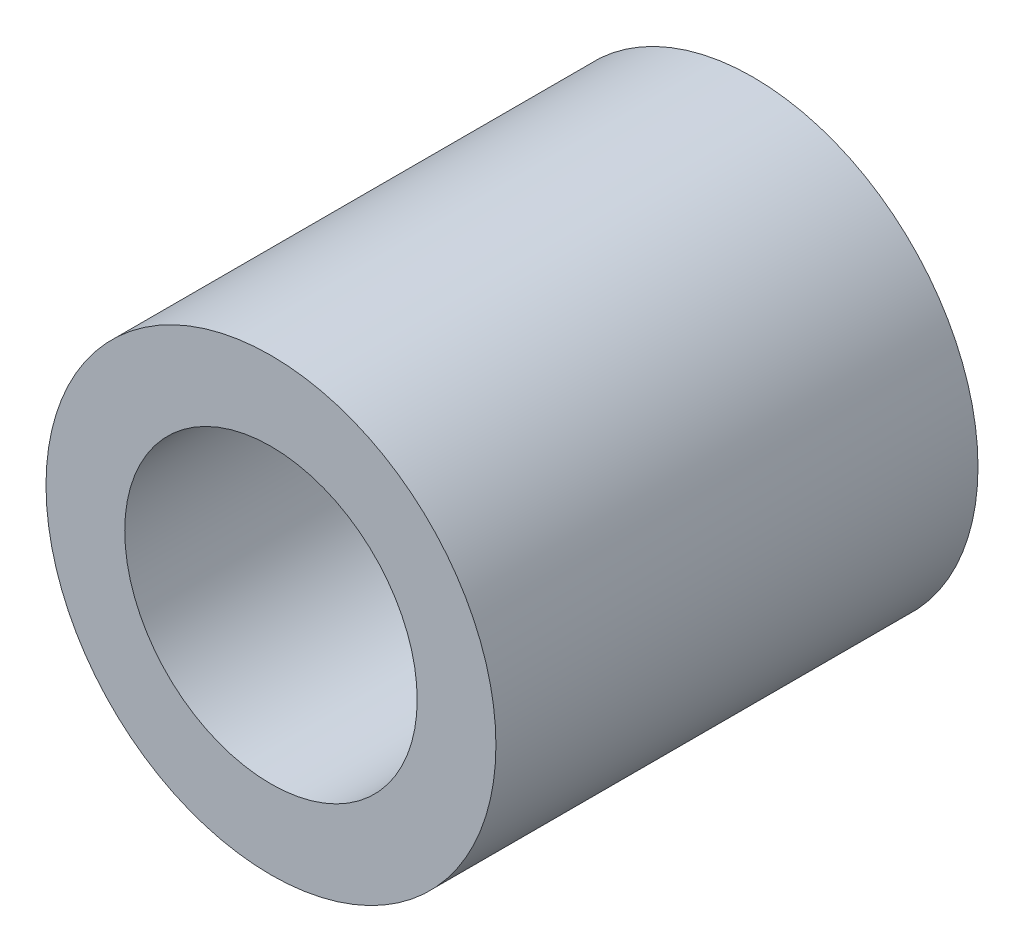
SolidWorks part; units mm, degrees
material "PVC Rigid"
ref_plane "Front" through (0, 0, 0) normal (0, 0, 1) x (1, 0, 0)
ref_plane "Top" through (0, 0, 0) normal (0, 1, 0) x (1, 0, 0)
ref_plane "Right" through (0, 0, 0) normal (1, 0, 0) x (0, 0, -1)
sketch "Sketch1" plane through (0, 0, 0) normal (0, 0, 1) x (1, 0, 0)
  circle A0 centre (0, 0) radius 6.9342
  circle A1 centre (0, 0) radius 10.668
  dimension "D1" = 21.336
  dimension "D2" = 13.8684
extrude "Boss-Extrude1" add sketch "Sketch1" along normal blind 22.86
